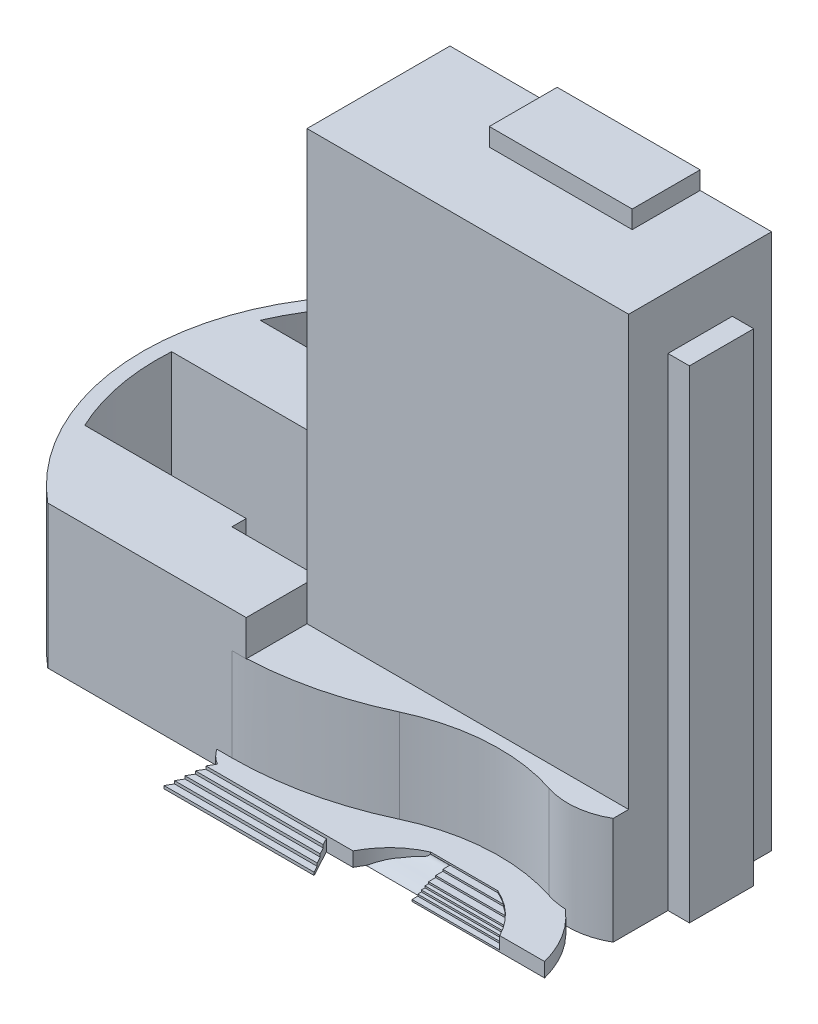
SolidWorks part; units mm, degrees
ref_plane "前视基准面" through (0, 0, 0) normal (0, 0, 1) x (1, 0, 0)
ref_plane "上视基准面" through (0, 0, 0) normal (0, 1, 0) x (1, 0, 0)
ref_plane "右视基准面" through (0, 0, 0) normal (1, 0, 0) x (0, 0, -1)
sketch "草图1" plane through (0, 0, 0) normal (0, 1, 0) x (1, 0, 0)
  line L0 (-42.8566, -25) -> (55.2262, -25) construction
  line L1 (9, 53.9481) -> (9, -76.8291) construction
  line L2 (-20.7666, -25) -> (52, -25)
  line L3 (52, -25) -> (52, -15)
  line L4 (52, -15) -> (-5, -15)
  line L5 (-5, -15) -> (-5, -13)
  line L6 (-5, -13) -> (-27.5908, -13)
  line L7 (-16, 20) -> (9, 20)
  line L8 (9, 20) -> (9, 31.229)
  line L9 (-16, 20) -> (-16, 25.9663)
  line L10 (-28.0401, 12) -> (4.5, 12)
  line L11 (9, 12) -> (9, 2)
  line L12 (9, 2) -> (3, 2)
  line L13 (6.5, 12) -> (6.5, 10)
  line L14 (6.5, 10) -> (4.5, 10)
  line L15 (4.5, 10) -> (4.5, 12)
  line L16 (6.5, 12) -> (9, 12)
  line L17 (-2, 2) -> (-2, 3.5)
  line L18 (-2, 3.5) -> (3, 3.5)
  line L19 (3, 3.5) -> (3, 2)
  line L20 (-2, 2) -> (-30.4344, 2)
  arc A0 (9, 31.229) -> (-20.7666, -25) centre (0, 0) ccw
  arc A1 (-16, 25.9663) -> (-28.0401, 12) centre (0, 0) ccw
  arc A2 (8.4462, 29.3072) -> (-19.4886, -23.4615) centre (0, 0) ccw construction
  arc A3 (-30.4344, 2) -> (-27.5908, -13) centre (0, 0) ccw
  dimension "D1" = 65
  dimension "D2" = 25
  dimension "D3" = 9
  dimension "D5" = 10
  dimension "D6" = 12
  dimension "D7" = 14
  dimension "D8" = 25
  dimension "D9" = 45
  dimension "D10" = 10
  dimension "D11" = 2
  dimension "D12" = 2
  dimension "D13" = 2.5
  dimension "D14" = 6
  dimension "D15" = 5
  dimension "D16" = 1.5
  dimension "D17" = 15
  dimension "D18" = 43
  dimension "D4" = 2
extrude "凸台-拉伸1" add sketch "草图1" along normal blind 20
sketch "草图3" plane through (0, 0, 0) normal (0, 1, 0) x (1, 0, 0)
  line L0 (7, 3.5) -> (52, 3.5)
  line L1 (52, 3.5) -> (52, -2)
  line L2 (52, -16.5) -> (7, -16.5)
  line L3 (7, 3.5) -> (7, -2)
  line L4 (4, -2) -> (7, -2)
  line L5 (4, -2) -> (4, -11)
  line L6 (4, -11) -> (7, -11)
  line L7 (52, -2) -> (55, -2)
  line L8 (55, -2) -> (55, -11)
  line L9 (55, -11) -> (52, -11)
  line L10 (9, -6.5) -> (68.2638, -6.5) construction
  line L11 (7, -11) -> (7, -16.5)
  line L12 (52, -11) -> (52, -16.5)
  line L13 (9, 2) -> (9, 12) construction
  dimension "D1" = 3
  dimension "D2" = 3
  dimension "D3" = 9
  dimension "D4" = 45
  dimension "D5" = 4.5
  dimension "D6" = 6.5
  dimension "D7" = 20
  dimension "D8" = 10
  dimension "D9" = 2
extrude "凸台-拉伸2" add sketch "草图3" along normal blind 75
sketch "草图4" plane through (0, 0, 11) normal (0, 0, 1) x (1, 0, 0)
  line L0 (4, 75) -> (7, 75)
  line L1 (7, 75) -> (7, 67.5)
  line L2 (7, 75) -> (7, 0) construction
  line L3 (7, 67.5) -> (4, 67.5)
  line L4 (4, 75) -> (4, 0) construction
  line L5 (4, 67.5) -> (4, 75)
  line L6 (52, 75) -> (52, 67.5)
  line L7 (52, 75) -> (52, 20) construction
  line L8 (52, 67.5) -> (55, 67.5)
  line L9 (55, 75) -> (55, 0) construction
  line L10 (55, 67.5) -> (55, 75)
  line L11 (55, 75) -> (52, 75)
  line L12 (7, 75) -> (52, 75) construction
  dimension "D1" = 7.5
extrude "切除-拉伸1" cut sketch "草图4" against normal up to next
sketch "草图9" plane through (0, 0, 0) normal (0, 1, 0) x (1, 0, 0)
  line L0 (52, -25) -> (52, -16.5) construction
  line L3 (52, -25) -> (52, -18.6603)
  line L4 (-20.7666, -25) -> (52, -25) construction
  line L5 (5, -25) -> (52, -25)
  arc A1 (43.892, -19.5048) -> (52, -18.6603) centre (47, -10) ccw
  arc A2 (43.892, -19.5048) -> (24.144, -20.7248) centre (35.5554, -45) ccw
  arc A3 (5, -25) -> (24.144, -20.7248) centre (5, 20) ccw
  dimension "D5" = 20
  dimension "D1" = 20
  dimension "D2" = 5
  dimension "D3" = 10
  dimension "D4" = 47
  dimension "D6" = 45
extrude "切除-拉伸3" cut sketch "草图9" along normal blind 15
sketch "草图10" plane through (0, 20, 0) normal (0, 1, 0) x (1, 0, 0)
  line L1 (52, -25) -> (7, -25)
  line L2 (52, -25) -> (52, -16.5)
  line L3 (52, -16.5) -> (7, -16.5)
  line L4 (7, -25) -> (7, -16.5)
extrude "切除-拉伸4" cut sketch "草图10" against normal blind 5
sketch "草图11" plane through (0, 0, 0) normal (0, 1, 0) x (1, 0, 0)
  line L0 (2, -31.5) -> (4.7443, -26.7598)
  line L1 (2, -31.5) -> (52, -31.5)
  line L3 (7.5, -16.5) -> (37, -16.5)
  arc A0 (52, -31.5) -> (37, -16.5) centre (37, -31.5) ccw
  arc A1 (7.5, -16.5) -> (4.7443, -26.7598) centre (7.5, -22) ccw
  dimension "D5" = 4.7402
  dimension "D1" = 50
  dimension "D2" = 15
  dimension "D3" = 22
  dimension "D4" = 16.5
  dimension "D6" = 2.7443
  dimension "D7" = 7.5
extrude "凸台-拉伸7" add sketch "草图11" along normal blind 2
ref_plane "基准面1" through (2, 0, 0) normal (1, 0, 0) x (0, 0, -1)
sketch "草图13" plane through (0, 2, 0) normal (0, 1, 0) x (1, 0, 0)
  line L0 (22.9956, -31.5) -> (20.9969, -27.7993)
  line L1 (2, -31.5) -> (52, -31.5) construction
  line L2 (20.9969, -27.7993) -> (54.018, -27.7993)
  line L3 (54.018, -27.7993) -> (54.018, -31.5)
  line L4 (54.018, -31.5) -> (22.9956, -31.5)
extrude "切除-拉伸5" cut sketch "草图13" against normal up to next
sketch "草图15" plane through (2, 0, 0) normal (1, 0, 0) x (0, 0, -1)
  line L0 (-31.5, 0) -> (-31.5, 0.4)
  line L1 (-31.5, 2) -> (-31.5, 0) construction
  line L2 (-31.5, 0.4) -> (-30.5743, 0.4)
  line L3 (-30.5743, 0.4) -> (-30.5743, 0.8)
  line L4 (-30.5743, 0.8) -> (-29.6493, 0.8)
  line L5 (-29.6493, 0.8) -> (-29.6493, 1.2)
  line L6 (-29.6493, 1.2) -> (-28.7243, 1.2)
  line L7 (-28.7243, 1.2) -> (-28.7243, 1.6)
  line L8 (-28.7243, 1.6) -> (-27.7993, 1.6)
  line L9 (-27.7993, 1.6) -> (-27.7993, 2)
  line L16 (-27.7993, 2) -> (-31.5, 2)
  line L17 (-31.5, 2) -> (-31.5, 0.4)
  line L19 (-27.7993, 0) -> (-27.7993, 2) construction
  dimension "D1" = 0.4
  dimension "D2" = 0.4
  dimension "D3" = 0.4
  dimension "D4" = 0.4
  dimension "D5" = 0.925
  dimension "D6" = 0.925
  dimension "D7" = 0.925
extrude "切除-拉伸6" cut sketch "草图15" along normal blind 21 contours L2 L3 L4 L5 L6 L7 L8 L9 L16 L17
sketch "草图16" plane through (0, 2, 0) normal (0, 1, 0) x (1, 0, 0)
  circle A0 centre (35, -33) radius 11.5
  dimension "D3" = 23
  dimension "D1" = 33
  dimension "D2" = 35
extrude "切除-拉伸7" cut sketch "草图16" against normal up to next
ref_plane "基准面2" through (35, 0, 0) normal (1, 0, 0) x (0, 0, -1)
sketch "草图18" plane through (35, 0, 0) normal (1, 0, 0) x (0, 0, -1)
  line L0 (-27.7993, 0.25) -> (-27.7993, 0)
  line L1 (-27.7993, 0) -> (-27.7993, 2) construction
  line L2 (-27.7993, 0.25) -> (-27, 0.25)
  line L3 (-27, 0.25) -> (-27, 0.5)
  line L4 (-27, 0.5) -> (-26.5, 0.5)
  line L5 (-26.5, 0.5) -> (-26.5, 0.75)
  line L6 (-26.5, 0.75) -> (-26, 0.75)
  line L7 (-26, 0.75) -> (-26, 1)
  line L8 (-26, 1) -> (-25.5, 1)
  line L9 (-25.5, 1) -> (-25.5, 1.25)
  line L10 (-25.5, 1.25) -> (-24.5, 1.25)
  line L11 (-24.5, 1.25) -> (-24.5, 1.5)
  line L12 (-24.5, 1.5) -> (-23.5, 1.5)
  line L13 (-23.5, 1.5) -> (-23.5, 1.75)
  line L14 (-23.5, 1.75) -> (-22.5, 1.75)
  line L16 (-22.5, 1.75) -> (-22.5, 2)
  line L22 (-27.7993, 0) -> (-21.5, 0)
  line L23 (-21.5, 0) -> (-21.5, 2)
  line L24 (-21.5, 2) -> (-22.5, 2)
  line L26 (-21.5, 2) -> (-27.7993, 2) construction
  dimension "D1" = 0.25
  dimension "D2" = 0.25
  dimension "D3" = 0.25
  dimension "D4" = 0.25
  dimension "D5" = 0.25
  dimension "D6" = 0.25
  dimension "D7" = 0.25
  dimension "D8" = 1
  dimension "D9" = 1
  dimension "D10" = 1
  dimension "D11" = 1
  dimension "D12" = 0.5
  dimension "D13" = 0.5
  dimension "D14" = 0.5
extrude "凸台-拉伸8" add sketch "草图18" along normal blind 11 and the other way blind 11 contours L22 L23 L24 L16 L14 L13 L12 L11 L10 L9 L8 L7 L6 L5 L4 L3 L2 L0
sketch "草图19" plane through (0, 0, 27.7993) normal (0, 0, 1) x (1, 0, 0)
  line L0 (24.7432, 2) -> (24.7432, 0)
  line L1 (20.9969, 0) -> (51.5363, 0) construction
  line L3 (30.3096, 2) -> (39.6904, 2) construction
  line L4 (24.7432, 2) -> (30.9006, 2)
ref_plane "基准面3" through (33, 0, 0) normal (1, 0, 0) x (0, 0, -1)
sketch "草图21" plane through (33, 0, 0) normal (1, 0, 0) x (0, 0, -1)
  line L2 (-27.7993, 0) -> (-19.9929, 0) construction
  line L3 (-27.7993, 0.25) -> (-27.7993, 2) construction
  line L6 (-22.5, 2) -> (-27.7993, 2.0437)
  line L7 (-27.7993, 2.0437) -> (-27.7993, 0)
  line L8 (-22.5, 2) -> (-27.7993, 2) construction
  spline S0 degree 3 poles (-27.7993, 0) (-27.2048, -0.2221) (-26.3847, 0.0786) (-25.3269, 0.4565) (-24.664, 0.7002) (-24.0211, 0.7999) (-23.2637, 1.2024) (-22.4997, 1.1833) (-22.5, 2) knots 0 0 0 0 0.297815 0.424941 0.570246 0.652882 0.75036 1 1 1 1
extrude "切除-拉伸8" cut sketch "草图21" against normal up to surface (8.2568 mm away)
sketch "草图22" plane through (0, 75, 0) normal (0, 1, 0) x (1, 0, 0)
  line L0 (52, 3.5) -> (7, 3.5) construction
  line L1 (22, 3.5) -> (42, 3.5)
  line L2 (22, 3.5) -> (22, -6)
  line L3 (22, -6) -> (42, -6)
  line L4 (42, 3.5) -> (42, -6)
  line L5 (52, -16.5) -> (52, 3.5) construction
  dimension "D1" = 20
  dimension "D2" = 9.5
  dimension "D3" = 10
extrude "凸台-拉伸9" add sketch "草图22" along normal blind 2.5
